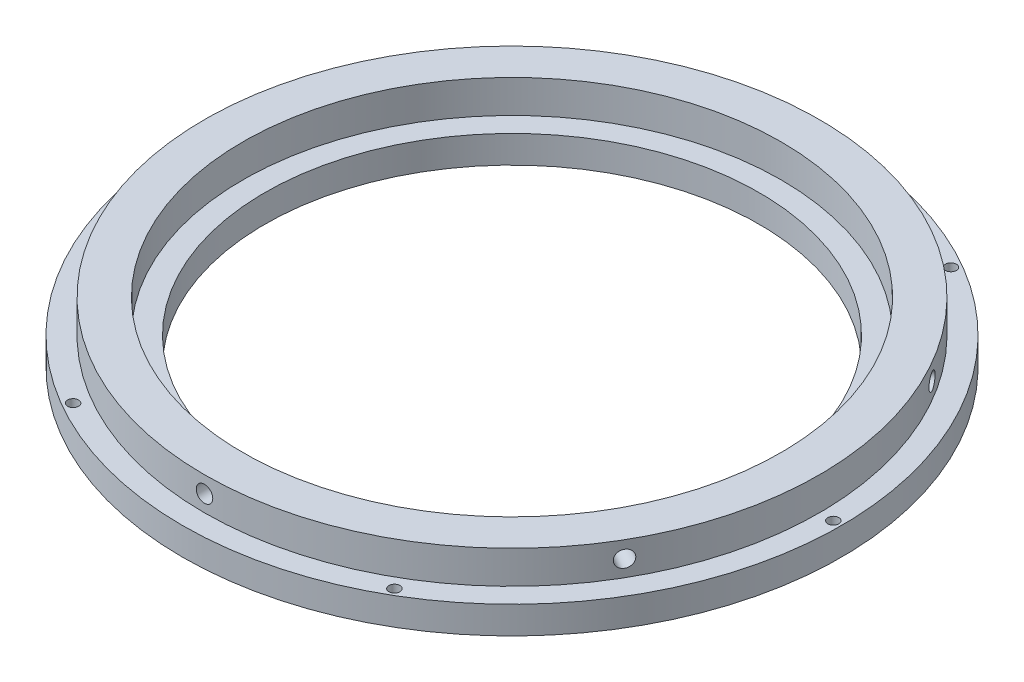
SolidWorks part; units mm, degrees
ref_plane "Front Plane" through (0, 0, 0) normal (0, 0, 1) x (1, 0, 0)
ref_plane "Top Plane" through (0, 0, 0) normal (0, 1, 0) x (1, 0, 0)
ref_plane "Right Plane" through (0, 0, 0) normal (1, 0, 0) x (0, 0, -1)
sketch "Sketch1" plane through (0, 0, 0) normal (0, 1, 0) x (1, 0, 0)
  circle A0 centre (0, 0) radius 76.2
  circle A1 centre (0, 0) radius 57.15
  dimension "D1" = 152.4
  dimension "D2" = 114.3
extrude "Boss-Extrude1" add sketch "Sketch1" along normal blind 6.35
sketch "Sketch2" plane through (0, 6.35, 0) normal (0, 1, 0) x (1, 0, 0)
  circle A0 centre (0, 0) radius 71.12
  circle A1 centre (0, 0) radius 76.2 construction
  circle A2 centre (0, 0) radius 62.23
  circle A3 centre (0, 0) radius 57.15 construction
  dimension "D1" = 5.08
  dimension "D2" = 5.08
extrude "Boss-Extrude2" add sketch "Sketch2" along normal blind 7.62
ref_plane "Plane1" through (0, 0, 71.12) normal (0, 0, 1) x (1, 0, 0)
sketch "Sketch4" plane through (0, 0, 71.12) normal (0, 0, 1) x (1, 0, 0)
  line L0 (0, -7.6835) -> (0, 7.6835) construction
  line L3 (71.12, 13.97) -> (-71.12, 13.97) construction
  circle A0 centre (0, 10.16) radius 1.905
  dimension "D1" = 3.81
  dimension "D2" = 3.81
extrude "Cut-Extrude1" cut sketch "Sketch4" against normal blind 5.08
pattern_circular "CirPattern1" count 6 over 360 about axis through (0, 0, 0) along (0, 1, 0) of "Cut-Extrude1"
sketch "Sketch7" plane through (0, 6.35, 0) normal (0, 1, 0) x (1, 0, 0)
  line L0 (0, 0) -> (50000, 0) construction
  line L1 (0, 0) -> (37.1475, 64.3414) construction
  circle A0 centre (37.1475, 64.3414) radius 1.27
  circle A1 centre (0, 0) radius 74.295 construction
  circle A2 centre (74.295, 0) radius 1.27
  circle A3 centre (37.1475, -64.3414) radius 1.27
  circle A4 centre (-37.1475, -64.3414) radius 1.27
  circle A5 centre (-74.295, 0) radius 1.27
  circle A6 centre (-37.1475, 64.3414) radius 1.27
  point P20 (0, 0)
  dimension "D1" = 2.54
  dimension "D2" = 148.59
  dimension "D3" = 60
  dimension "D4" = 6
extrude "Cut-Extrude2" cut sketch "Sketch7" against normal blind 2.54
